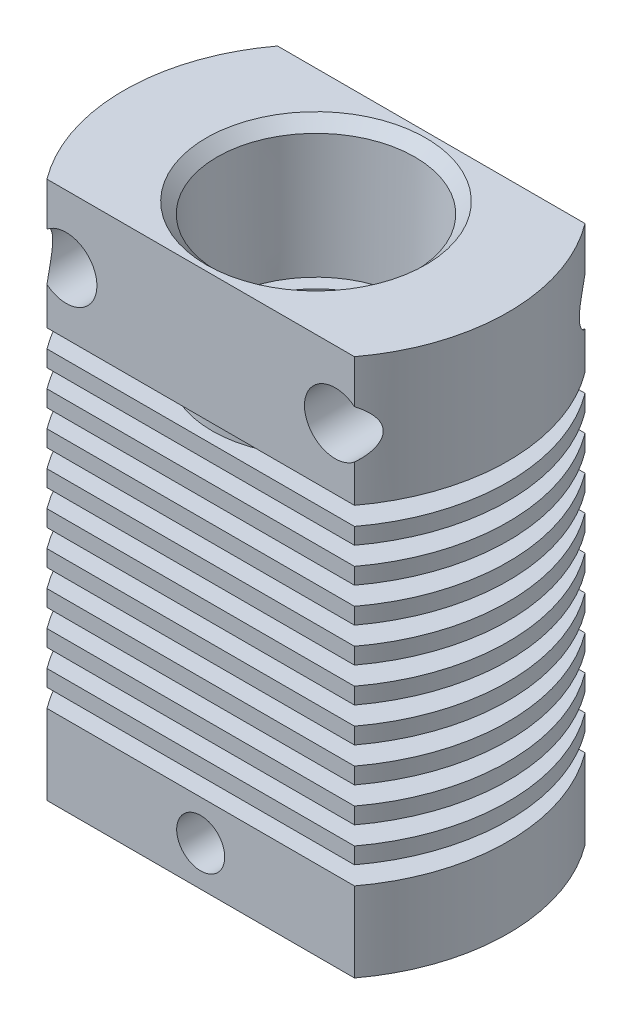
SolidWorks part; units mm, degrees
ref_plane "Front Plane" through (0, 0, 0) normal (0, 0, 1) x (1, 0, 0)
ref_plane "Top Plane" through (0, 0, 0) normal (0, 1, 0) x (1, 0, 0)
ref_plane "Right Plane" through (0, 0, 0) normal (1, 0, 0) x (0, 0, -1)
sketch "Sketch1" plane through (0, 0, 0) normal (0, 1, 0) x (1, 0, 0)
  line L1 (-8, 6) -> (8, 6)
  line L3 (-8, -6) -> (8, -6)
  line L5 (-8, 6) -> (8, -6) construction
  line L6 (-8, -6) -> (8, 6) construction
  arc A0 (-8, 6) -> (-8, -6) centre (0, 0) ccw
  arc A1 (8, -6) -> (8, 6) centre (0, 0) ccw
  dimension "D1" = 20
  dimension "D2" = 12
extrude "Boss-Extrude1" add sketch "Sketch1" along normal mid plane 28
ref_plane "Plane1" through (0, 7.3, 0) normal (0, 1, 0) x (1, 0, 0)
sketch "Sketch2" plane through (0, 7.3, 0) normal (0, 1, 0) x (1, 0, 0)
  line L2 (8, 6) -> (-8, 6)
  line L3 (-8, -6) -> (8, -6)
  line L4 (8, 6) -> (-8, 6)
  line L5 (-8, -6) -> (8, -6)
  arc A2 (8, -6) -> (8, 6) centre (0, 0) ccw
  arc A3 (-8, 6) -> (-8, -6) centre (0, 0) ccw
  arc A4 (8, -6) -> (8, 6) centre (0, 0) ccw
  arc A5 (-8, 6) -> (-8, -6) centre (0, 0) ccw
  dimension "D1" = 0
extrude "Cut-Extrude1" cut sketch "Sketch2" against normal blind 0.95
pattern_linear "LPattern1" count 10 spacing 1.8 along (0, -1, 0) of "Cut-Extrude1"
sketch "Sketch3" plane through (0, 0, 6) normal (0, 0, 1) x (1, 0, 0)
  line L0 (0, 14) -> (0, 10.5) construction
  line L1 (-8, 14) -> (8, 14) construction
  line L2 (-7, 10.5) -> (7, 10.5) construction
  circle A0 centre (7, 10.5) radius 1.6
  circle A1 centre (-7, 10.5) radius 1.6
  dimension "D1" = 3.2
  dimension "D2" = 14
  dimension "D3" = 3.5
extrude "Cut-Extrude2" cut sketch "Sketch3" against normal through all
sketch "Sketch4" plane through (0, 14, 0) normal (0, 1, 0) x (1, 0, 0)
  circle A0 centre (0, 0) radius 5.4
  dimension "D1" = 10.8
extrude "Boss-Extrude2" add sketch "Sketch4" against normal up to surface (7.65 mm away) up to face at (0, 6.35, 0)
sketch "Sketch5" plane through (0, 14, 0) normal (0, 1, 0) x (1, 0, 0)
  circle A0 centre (0, 0) radius 4.5
  dimension "D1" = 9
extrude "Boss-Extrude3" add sketch "Sketch5" against normal up to surface (23.85 mm away) up to face at (0, -9.85, 0)
hole_wizard "1/8 NPT Tapped Hole1" positions "Sketch6" profile "Sketch7" size "1/8" standard "ANSI Inch"
sketch "Sketch6" plane through (0, 14, 0) normal (0, 1, 0) x (1, 0, 0)
  point P2 (0, 0)
sketch "Sketch7" plane through (0, 14, 0) normal (1, 0, 0) x (0, 0, 1)
  line L0 (0, 0) -> (0, 9.6335)
  line L1 (4.2164, 7.1) -> (0, 9.6335)
  line L2 (-4.2164, 7.1) -> (0, 9.6335) construction
  line L3 (4.2164, 7.1) -> (4.2164, 6.92)
  line L4 (4.2164, 6.92) -> (4.9533, 6.92)
  line L5 (4.9533, 6.92) -> (5.1434, 0.5716)
  line L6 (5.1434, 0.5716) -> (5.715, 0)
  line L7 (5.715, 0) -> (0, 0)
  line L8 (0, -6.35) -> (0, 107.95) construction
  line L9 (-5.1434, 0.5716) -> (-5.715, 0) construction
  line L11 (-4.2164, 6.92) -> (-4.9533, 6.92) construction
  line L12 (-4.9533, 6.92) -> (-5.1434, 0.5716) construction
  dimension "Tap Drill Dia." = 8.4328
  dimension "Tap Drill Depth" = 7.1
  dimension "Thread Dia." = 10.2867
  dimension "Thread Angle" = 3.43
  dimension "Thread Depth" = 6.92
  dimension "C'Sink Dia." = 11.43
  dimension "C'Sink Angle" = 90
  dimension "Drill Angle" = 118
sketch "Sketch10" plane through (0, 14, 0) normal (0, 1, 0) x (1, 0, 0)
  circle A0 centre (0, 0) radius 2.5
  dimension "D1" = 5
extrude "Cut-Extrude6" cut sketch "Sketch10" against normal through all
sketch "Sketch9" plane through (0, -14, 0) normal (0, -1, 0) x (1, 0, 0)
  circle A0 centre (0, 0) radius 3.5
  dimension "D1" = 7
extrude "Cut-Extrude5" cut sketch "Sketch9" against normal blind 17
hole_wizard "M3x0.5 Tapped Hole1" positions "Sketch11" profile "Sketch12" tap size "M3x0.5" standard "ANSI Metric"
sketch "Sketch11" plane through (0, 0, 6) normal (0, 0, -1) x (-1, 0, 0)
  line L0 (0, -14) -> (0, -9.85) construction
  line L1 (-8, -14) -> (8, -14) construction
  line L2 (-8, -9.85) -> (8, -9.85) construction
  point P11 (0, -11.925)
sketch "Sketch12" plane through (0, -11.925, 6) normal (1, 0, 0) x (0, -1, 0)
  line L0 (0, 0) -> (0, 2.5)
  line L1 (0, 2.5) -> (1.25, 2.5)
  line L2 (1.25, 2.5) -> (1.25, 0)
  line L5 (1.25, 0) -> (0, 0)
  line L11 (0, -6.35) -> (0, 107.95) construction
  dimension "Thru Tap Drill Dia." = 2.5
  dimension "Thru Tap Drill Depth" = 2.5
cosmetic thread "Hole Thread1" parameters "D2"=3
hole_wizard "M3x0.5 Tapped Hole2" positions "Sketch15" profile "Sketch14" tap size "M3x0.5" standard "ANSI Metric"
sketch "Sketch15" plane through (0, -14, 0) normal (0, -1, 0) x (-1, 0, 0)
  line L0 (0, 6) -> (0, 1.7) construction
  line L4 (7, 1.7) -> (-7, 1.7) construction
  line L5 (-8, 6) -> (8, 6) construction
  point P11 (-7, 1.7)
  point P14 (6.8597, 1.7)
  dimension "D1" = 4.3
  dimension "D2" = 14
sketch "Sketch14" plane through (-6.8597, -14, -1.7) normal (1, 0, 0) x (0, 0, -1)
  line L0 (0, 0) -> (0, 4.15)
  line L1 (0, 4.15) -> (1.25, 4.15)
  line L2 (1.25, 4.15) -> (1.25, 0.25)
  line L3 (1.25, 0.25) -> (1.5, 0)
  line L5 (1.5, 0) -> (0, 0)
  line L6 (-1.25, 0.25) -> (-1.5, 0) construction
  line L11 (0, -6.35) -> (0, 107.95) construction
  dimension "Thru Tap Drill Dia." = 2.5
  dimension "Thru Tap Drill Depth" = 4.15
  dimension "Near C'Sink Dia." = 3
  dimension "Near C'Sink Angle" = 90
cosmetic thread "Hole Thread4" parameters "D2"=3
cosmetic thread "Hole Thread5" parameters "D2"=3
